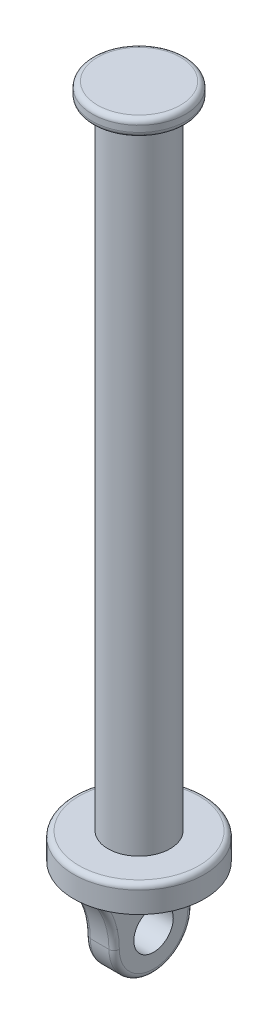
SolidWorks part; units mm, degrees
ref_plane "Front Plane" through (0, 0, 0) normal (0, 0, 1) x (1, 0, 0)
ref_plane "Top Plane" through (0, 0, 0) normal (0, 1, 0) x (1, 0, 0)
ref_plane "Right Plane" through (0, 0, 0) normal (1, 0, 0) x (0, 0, -1)
sketch "Sketch1" plane through (0, 0, 0) normal (0, 1, 0) x (1, 0, 0)
  circle A0 centre (0, 0) radius 15
  dimension "D1" = 30
extrude "Boss-Extrude1" add sketch "Sketch1" along normal blind 305
sketch "Sketch2" plane through (0, 305, 0) normal (0, 1, 0) x (1, 0, 0)
  circle A0 centre (0, 0) radius 22.5
  dimension "D1" = 45
extrude "Boss-Extrude2" add sketch "Sketch2" along normal blind 8
sketch "Sketch3" plane through (0, 0, 0) normal (0, -1, 0) x (1, 0, 0)
  circle A0 centre (0, 0) radius 31.5
  dimension "D1" = 63
extrude "Boss-Extrude3" add sketch "Sketch3" along normal blind 12.7
sketch "Sketch4" plane through (0, 0, 0) normal (1, 0, 0) x (0, 0, -1)
  line L0 (0, 0) -> (0, -86.2941) construction
  line L1 (-28.5, -12.7) -> (28.5, -12.7)
  line L2 (-31.5, -12.7) -> (31.5, -12.7) construction
  circle A0 centre (0, -37.7) radius 9.5
  arc A1 (-18.9999, -37.7449) -> (18.9999, -37.7449) centre (0, -37.7) ccw
  arc A2 (18.9999, -37.7449) -> (28.5, -12.7) centre (56.9998, -37.8348) cw
  arc A3 (-18.9999, -37.7449) -> (-28.5, -12.7) centre (-56.9998, -37.8348) ccw
  point P5 (16.5709, -37.7)
  point P15 (0, -12.7)
  dimension "D2" = 19
  dimension "D4" = 38
  dimension "D5" = 19
  dimension "D1" = 25
  dimension "D3" = 57
extrude "Boss-Extrude5" add sketch "Sketch4" along normal mid plane 14
fillet "Fillet1" radius 2.5 9 edges at (-7, -24.3576, 21.4701) (-7, -56.7, 0) (7, -24.3576, 21.4701) (7, -56.7, 0) (0, 313, 22.5) (-7, -24.3576, -21.4701) (7, -24.3576, -21.4701) (0, 0, -31.5) (0, 305, 22.5)
